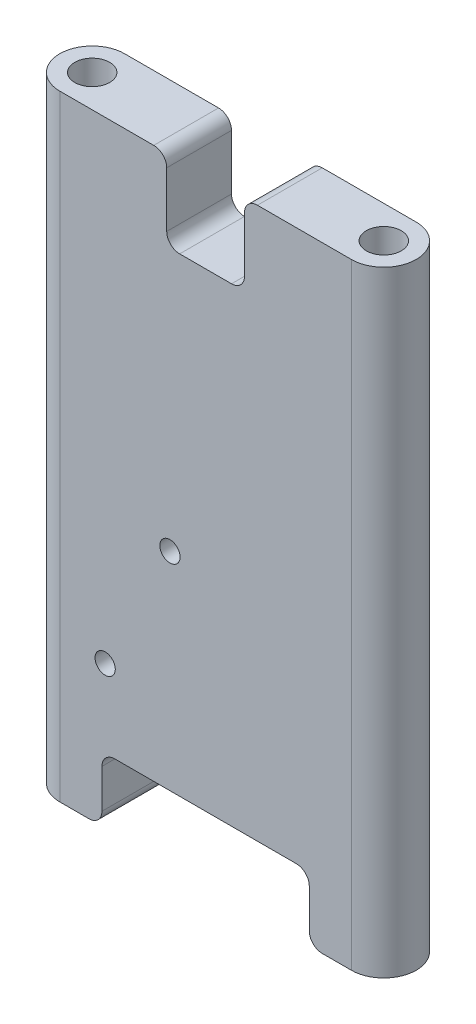
SolidWorks part; units mm, degrees
ref_plane "Front Plane" through (0, 0, 0) normal (0, 0, 1) x (1, 0, 0)
ref_plane "Top Plane" through (0, 0, 0) normal (0, 1, 0) x (1, 0, 0)
ref_plane "Right Plane" through (0, 0, 0) normal (1, 0, 0) x (0, 0, -1)
sketch "Sketch1" plane through (0, 0, 0) normal (0, 1, 0) x (1, 0, 0)
  line L0 (-28.575, 0) -> (28.575, 0) construction
  line L1 (-55, 0) -> (55, 0) construction
  line L2 (-28.575, 6.35) -> (28.575, 6.35)
  line L3 (-28.575, -6.35) -> (28.575, -6.35)
  arc A0 (-28.575, 6.35) -> (-28.575, -6.35) centre (-28.575, 0) ccw
  arc A1 (28.575, -6.35) -> (28.575, 6.35) centre (28.575, 0) ccw
  circle A2 centre (28.575, 0) radius 3.429
  circle A3 centre (-28.575, 0) radius 3.429
  point P5 (0, 0)
  dimension "D2" = 6.35
  dimension "D3" = 6.858
  dimension "D4" = 6.858
  dimension "D1" = 57.15
extrude "Boss-Extrude1" add sketch "Sketch1" along normal mid plane 120.65
sketch "Sketch2" plane through (0, 0, 0) normal (0, 0, 1) x (1, 0, 0)
  line L0 (-7.62, 60.325) -> (-7.62, 44.45)
  line L1 (-28.575, 60.325) -> (28.575, 60.325) construction
  line L2 (-7.62, 44.45) -> (7.62, 44.45)
  line L3 (7.62, 44.45) -> (7.62, 60.325)
  point P4 (-7.62, 52.3875)
  dimension "D1" = 7.62
  dimension "D2" = 7.62
  dimension "D3" = 15.875
extrude "Cut-Extrude1" cut sketch "Sketch2" against normal through all both and the other way through all
fillet "Fillet1" radius 2.54 4 edges at (7.62, 60.325, 0) (7.62, 44.45, 0) (-7.62, 44.45, 0) (-7.62, 60.325, 0)
sketch "Sketch5" plane through (0, 0, 6.35) normal (0, 0, 1) x (1, 0, 0)
  line L0 (-28.575, -60.325) -> (28.575, -60.325) construction
  line L1 (-20.32, -60.325) -> (20.32, -60.325)
  line L2 (-20.32, -60.325) -> (-20.32, -47.625)
  line L3 (-20.32, -47.625) -> (20.32, -47.625)
  line L4 (20.32, -60.325) -> (20.32, -47.625)
  point P6 (0, -47.625)
  dimension "D1" = 40.64
  dimension "D2" = 12.7
extrude "Cut-Extrude3" cut sketch "Sketch5" against normal through all both
fillet "Fillet2" radius 2.54 4 edges at (20.32, -60.325, 0) (-20.32, -60.325, 0) (-20.32, -47.625, 0) (20.32, -47.625, 0)
sketch "Sketch4" plane through (0, 0, 6.35) normal (0, 0, 1) x (1, 0, 0)
  line L3 (17.78, -47.625) -> (-17.78, -47.625) construction
  line L6 (-28.575, 60.325) -> (-28.575, -60.325) construction
  circle A0 centre (-6.985, -6.985) radius 1.9844
  circle A1 centre (-19.685, -32.385) radius 1.9844
  point P4 (-18.832, -27.9793)
  dimension "D1" = 3.9688
  dimension "D2" = 3.9688
  dimension "D3" = 25.4
  dimension "D4" = 12.7
  dimension "D5" = 15.24
  dimension "D6" = 8.89
extrude "Cut-Extrude2" cut sketch "Sketch4" against normal blind 6.35
sketch "Sketch6" plane through (0, 0, -6.35) normal (0, 0, -1) x (-1, 0, 0)
  line L0 (28.575, 60.325) -> (28.575, -60.325) construction
  circle A0 centre (5.08, 35.7111) radius 1.9844
  circle A1 centre (20.955, 35.7111) radius 1.9844
  circle A2 centre (5.08, -40.4889) radius 1.9844
  circle A3 centre (20.955, -40.4889) radius 1.9844
  point P8 (0, 0)
  point P9 (0, 0)
  point P10 (0, 0)
  point P11 (0, 0)
  point P12 (0, 0)
  dimension "D4" = 3.9688
  dimension "D1" = 15.875
  dimension "D2" = 76.2
  dimension "D3" = 7.62
extrude "Cut-Extrude4" cut sketch "Sketch6" against normal blind 6.35
sketch "Sketch7" plane through (0, 0, -6.35) normal (0, 0, -1) x (-1, 0, 0)
  line L0 (-28.575, 60.325) -> (-28.575, -60.325) construction
  line L1 (-17.78, -47.625) -> (17.78, -47.625) construction
  circle A0 centre (-15.875, 15.875) radius 1.9844
  circle A1 centre (-15.875, -22.225) radius 1.9844
  point P4 (0, 0)
  point P5 (0, 0)
  dimension "D1" = 3.9688
  dimension "D2" = 12.7
  dimension "D3" = 25.4
  dimension "D4" = 38.1
extrude "Cut-Extrude5" cut sketch "Sketch7" against normal blind 6.35
equation "\"D4@Sketch1\"=\"D3@Sketch1\""
